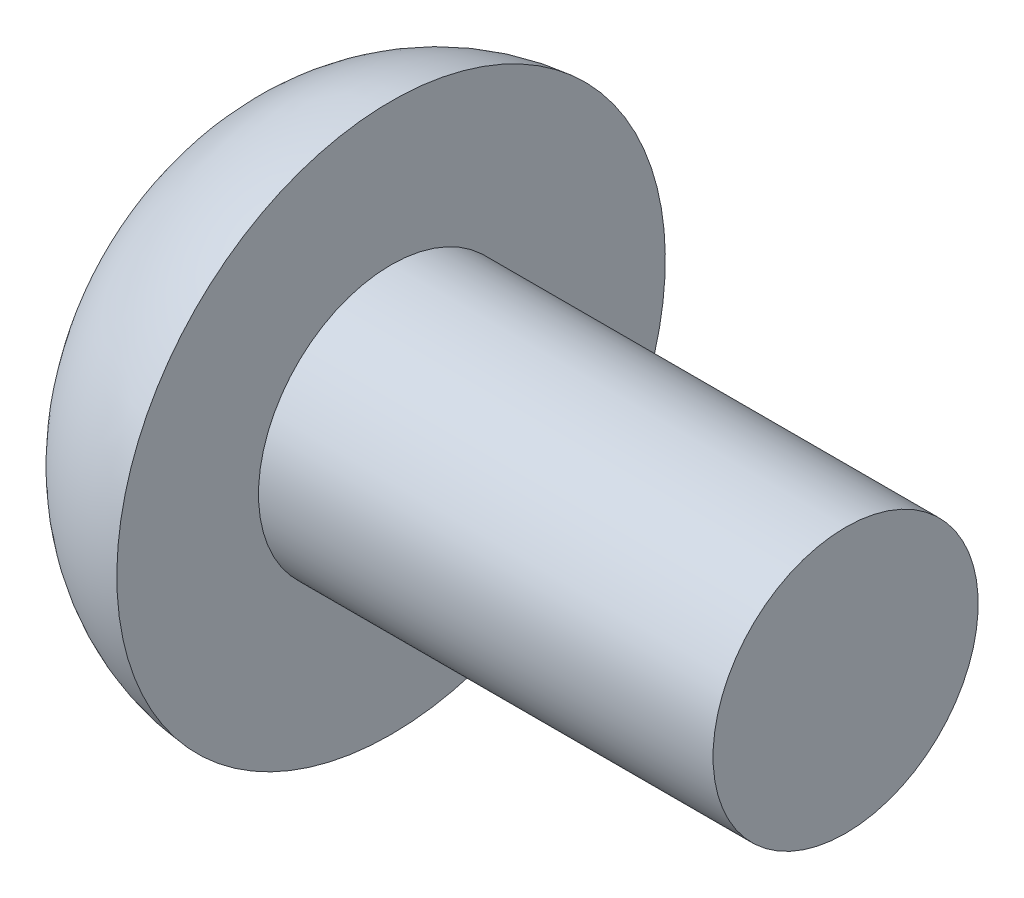
SolidWorks part; units mm, degrees
material "碳钢"
ref_plane "前视基准面" through (0, 0, 0) normal (0, 0, 1) x (1, 0, 0)
ref_plane "上视基准面" through (0, 0, 0) normal (0, 1, 0) x (1, 0, 0)
ref_plane "右视基准面" through (0, 0, 0) normal (1, 0, 0) x (0, 0, -1)
sketch "草图1" plane through (0, 0, 0) normal (0, 0, 1) x (1, 0, 0)
  line L0 (0, 0) -> (0, 2.2)
  line L1 (2.2, 3.62) -> (2.2, 1.75)
  line L2 (2.2, 1.75) -> (8.2, 1.75)
  line L3 (8.2, 1.75) -> (8.2, 0)
  line L4 (8.2, 0) -> (0, 0) construction
  line L5 (2.2, 3.62) -> (-1.0353, 3.4504) construction
  line L6 (0, 0) -> (8.2, 0)
  arc A1 (2.2, 3.62) -> (0, 2.2) centre (2.4125, 0.8765) ccw
  dimension "D6" = 2.7517
  dimension "D1" = 2.2
  dimension "D2" = 7.24
  dimension "D3" = 3
  dimension "D4" = 3.5
  dimension "D5" = 6
  dimension "D7" = 2.2
revolve "旋转1" add sketch "草图1" angle 360 about L6
cosmetic thread "装饰螺纹线1" parameters "D2"=2.5
sketch "草图2" plane through (0, 0, 0) normal (-1, 0, 0) x (0, 0, 1)
  line L1 (0, 1.1547) -> (-1, 0.5774)
  line L2 (-1, 0.5774) -> (-1, -0.5774)
  line L3 (-1, -0.5774) -> (0, -1.1547)
  line L4 (0, -1.1547) -> (1, -0.5774)
  line L5 (1, -0.5774) -> (1, 0.5774)
  line L6 (1, 0.5774) -> (0, 1.1547)
  circle A0 centre (0, 0) radius 1 construction
  dimension "D1" = 2
extrude "切除-拉伸1" cut sketch "草图2" against normal blind 1
